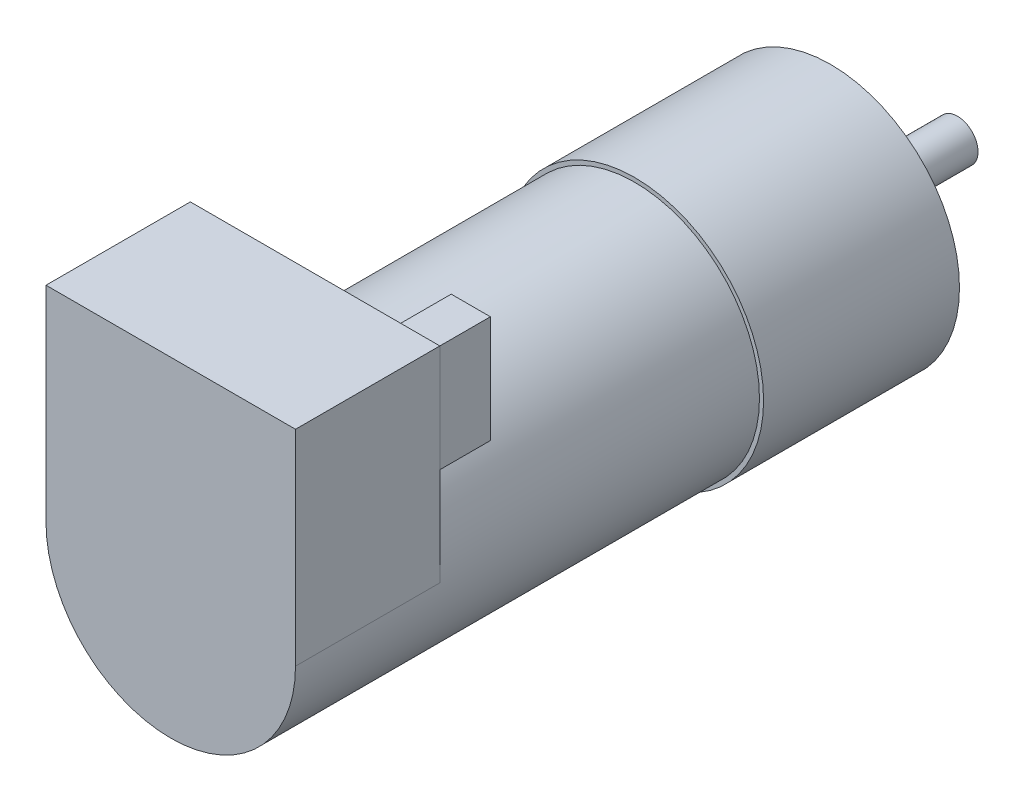
SolidWorks part; units mm, degrees
ref_plane "Front Plane" through (0, 0, 0) normal (0, 0, 1) x (1, 0, 0)
ref_plane "Top Plane" through (0, 0, 0) normal (0, 1, 0) x (1, 0, 0)
ref_plane "Right Plane" through (0, 0, 0) normal (1, 0, 0) x (0, 0, -1)
sketch "Sketch1" plane through (0, 0, 0) normal (0, 0, 1) x (1, 0, 0)
  circle A0 centre (0, 0) radius 12.5
  dimension "D1" = 25
extrude "Boss-Extrude1" add sketch "Sketch1" along normal blind 19
sketch "Sketch2" plane through (0, 0, 19) normal (0, 0, 1) x (1, 0, 0)
  circle A0 centre (0, 0) radius 12.1
  dimension "D1" = 24.2
extrude "Boss-Extrude2" add sketch "Sketch2" along normal blind 31
sketch "Sketch3" plane through (0, 0, 50) normal (0, 0, 1) x (1, 0, 0)
  line L0 (-12.1, 0) -> (-12.1, 19.9)
  line L1 (-12.1, 19.9) -> (12.1, 19.9)
  line L2 (12.1, 19.9) -> (12.1, 0)
  arc A0 (-12.1, 0) -> (12.1, 0) centre (0, 0) ccw
  point P1 (0, -12.1)
  dimension "D1" = 19.9
extrude "Boss-Extrude3" add sketch "Sketch3" along normal blind 14
sketch "Sketch4" plane through (0, 0, 50) normal (0, 0, -1) x (-1, 0, 0)
  line L2 (-12, 19.8) -> (-12, 9.4)
  line L3 (-12, 9.4) -> (-8.2, 9.4)
  line L4 (-8.2, 19.8) -> (-8.2, 9.4)
  line L5 (-12.1, 0) -> (-12.1, 19.9) construction
  line L6 (-12, 19.8) -> (-8.2, 19.8)
  line L7 (-12.1, 19.9) -> (12.1, 19.9) construction
  dimension "D1" = 3.8
  dimension "D2" = 10.4
  dimension "D3" = 0.1
  dimension "D4" = 0.1
extrude "Boss-Extrude4" add sketch "Sketch4" along normal blind 5
sketch "Sketch5" plane through (0, 0, 0) normal (0, 0, -1) x (-1, 0, 0)
  circle A0 centre (0, 0) radius 3.5
  dimension "D1" = 7
extrude "Boss-Extrude5" add sketch "Sketch5" along normal blind 2.7
sketch "Sketch6" plane through (0, 0, 0) normal (0, 0, -1) x (-1, 0, 0)
  circle A0 centre (0, 0) radius 2
  dimension "D1" = 4
extrude "Boss-Extrude6" add sketch "Sketch6" along normal blind 12.3
sketch "Sketch7" plane through (0, 0, 0) normal (0, 0, -1) x (-1, 0, 0)
  line L0 (0, 0) -> (8.8388, 8.8388) construction
  line L1 (0, 0) -> (0, 12.5) construction
  circle A0 centre (0, 0) radius 12.5 construction
  circle A1 centre (6.0104, 6.0104) radius 1.5
  circle A2 centre (-6.0104, -6.0104) radius 1.5
  point P13 (0, 0)
  dimension "D2" = 8.5
  dimension "D3" = 3
  dimension "D1" = 45
  dimension "D4" = 2
extrude "Cut-Extrude1" cut sketch "Sketch7" against normal blind 5
